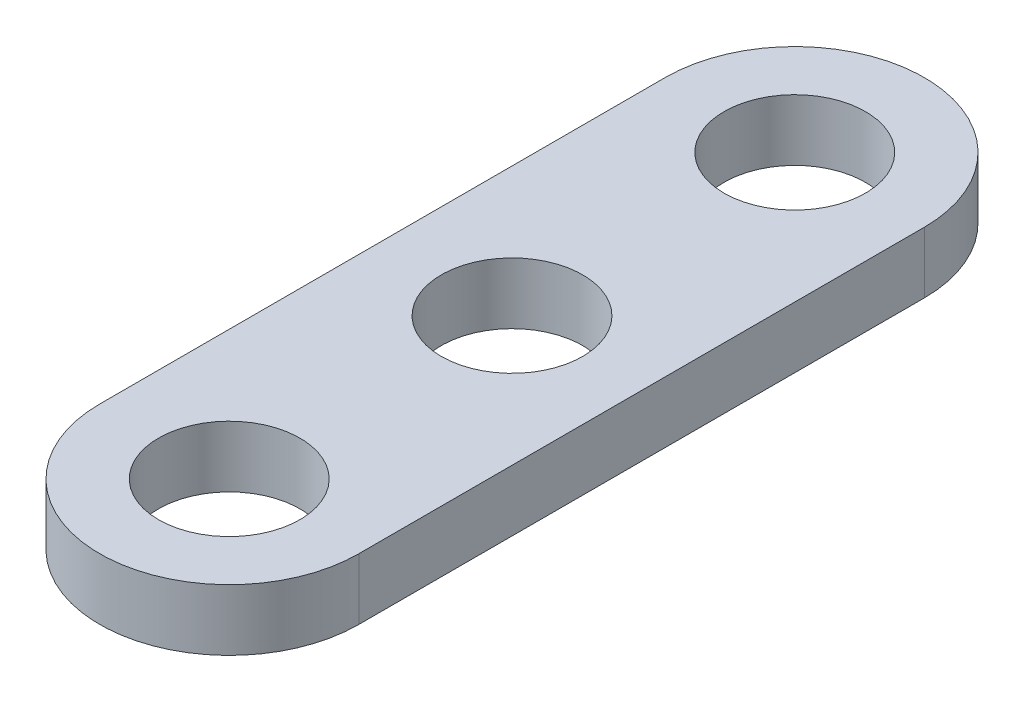
SolidWorks part; units mm, degrees
ref_plane "前视基准面" through (0, 0, 0) normal (0, 0, 1) x (1, 0, 0)
ref_plane "上视基准面" through (0, 0, 0) normal (0, 1, 0) x (1, 0, 0)
ref_plane "右视基准面" through (0, 0, 0) normal (1, 0, 0) x (0, 0, -1)
other "Configuration Table"
sketch "草图1" plane through (0, 0, 0) normal (0, 1, 0) x (1, 0, 0)
  line L0 (0, -12) -> (0, 12) construction
  line L1 (-5.5, -12) -> (-5.5, 12)
  line L2 (5.5, -12) -> (5.5, 12)
  arc A0 (-5.5, -12) -> (5.5, -12) centre (0, -12) ccw
  arc A1 (5.5, 12) -> (-5.5, 12) centre (0, 12) ccw
  circle A2 centre (0, 12) radius 3
  circle A3 centre (0, -12) radius 3
  circle A4 centre (0, 0) radius 3
  point P2 (0, 0)
  dimension "D2" = 5.5
  dimension "D3" = 6
  dimension "D1" = 24
extrude "凸台-拉伸2" add sketch "草图1" along normal blind 2.6
